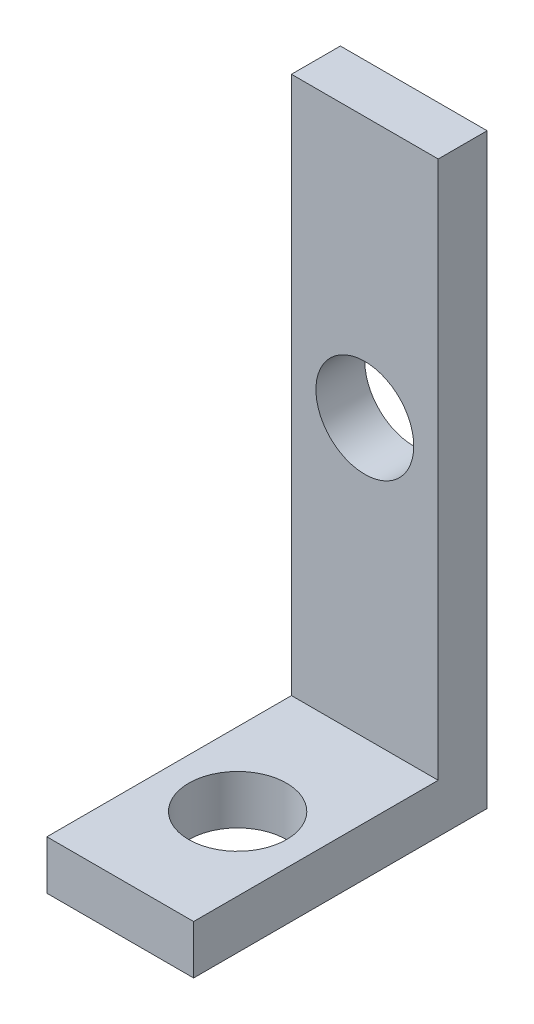
SolidWorks part; units mm, degrees
ref_plane "Front Plane" through (0, 0, 0) normal (0, 0, 1) x (1, 0, 0)
ref_plane "Top Plane" through (0, 0, 0) normal (0, 1, 0) x (1, 0, 0)
ref_plane "Right Plane" through (0, 0, 0) normal (1, 0, 0) x (0, 0, -1)
sketch "Sketch1" plane through (0, 0, 0) normal (0, 0, 1) x (1, 0, 0)
  line L1 (0, 0) -> (3.81, 0)
  line L2 (0, 0) -> (0, 15.24)
  line L3 (0, 15.24) -> (3.81, 15.24)
  line L4 (3.81, 0) -> (3.81, 15.24)
extrude "Boss-Extrude1" add sketch "Sketch1" along normal blind 1.27
sketch "Sketch2" plane through (0, 0, 1.27) normal (0, 0, 1) x (1, 0, 0)
  line L0 (3.81, 0) -> (3.81, 15.24) construction
  line L1 (0, 0) -> (3.81, 0)
  line L2 (0, 0) -> (0, 1.27)
  line L3 (0, 1.27) -> (3.81, 1.27)
  line L4 (3.81, 0) -> (3.81, 1.27)
extrude "Boss-Extrude2" add sketch "Sketch2" along normal blind 6.35
sketch "Sketch4" plane through (0, 0, 1.27) normal (0, 0, 1) x (1, 0, 0)
  circle A0 centre (1.905, 8.4667) radius 1.27
sketch "Sketch6" plane through (0, 1.27, 0) normal (0, 1, 0) x (1, 0, 0)
  circle A0 centre (1.905, -4.572) radius 1.27
extrude "Cut-Extrude1" cut sketch "Sketch6" against normal blind 6.35
extrude "Cut-Extrude2" cut sketch "Sketch4" against normal blind 6.35
